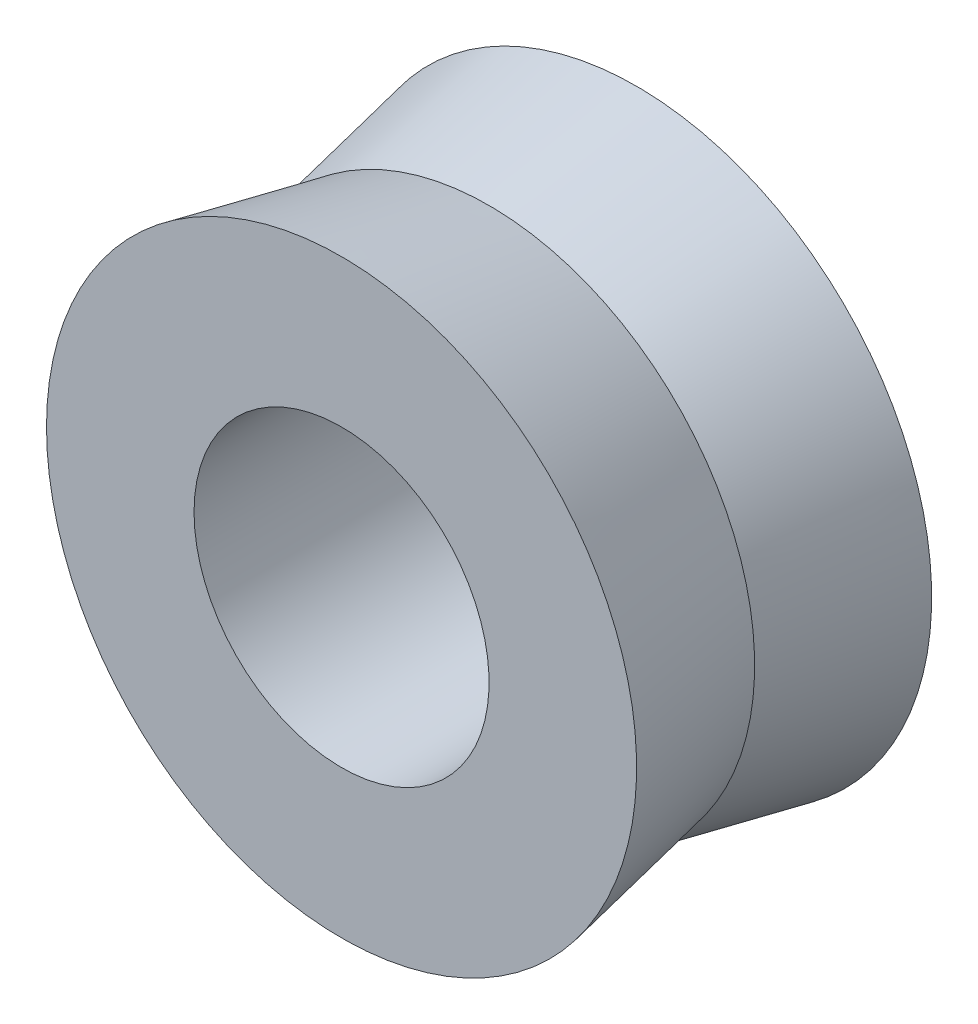
SolidWorks part; units mm, degrees
ref_plane "Front Plane" through (0, 0, 0) normal (0, 0, 1) x (1, 0, 0)
ref_plane "Top Plane" through (0, 0, 0) normal (0, 1, 0) x (1, 0, 0)
ref_plane "Right Plane" through (0, 0, 0) normal (1, 0, 0) x (0, 0, -1)
sketch "Sketch1" plane through (0, 0, 0) normal (0, 1, 0) x (1, 0, 0)
  line L0 (0, 0) -> (-12.7, 0)
  line L1 (-12.7, 0) -> (-12.7, 12.7)
  line L2 (-12.7, 12.7) -> (0, 12.7)
  line L3 (0, 12.7) -> (0, 0)
  line L4 (-12.7, 6.35) -> (0, 6.35)
  line L5 (-6.35, 12.7) -> (-6.35, 0)
  line L6 (-12.7, 12.7) -> (-11.43, 6.35)
  line L7 (-11.43, 6.35) -> (-12.7, 0)
  dimension "D1" = 12.7
  dimension "D2" = 12.7
  dimension "D3" = 1.27
revolve "Revolve1" add sketch "Sketch1" angle 360 about L3
